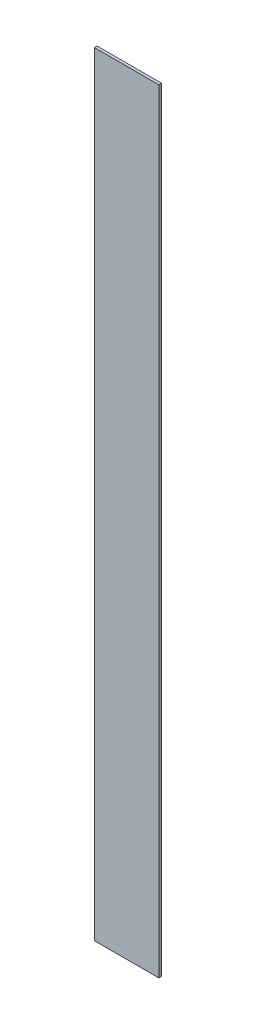
SolidWorks part; units mm, degrees
ref_plane "Front Plane" through (0, 0, 0) normal (0, 0, 1) x (1, 0, 0)
ref_plane "Top Plane" through (0, 0, 0) normal (0, 1, 0) x (1, 0, 0)
ref_plane "Right Plane" through (0, 0, 0) normal (1, 0, 0) x (0, 0, -1)
sketch "Sketch1" plane through (0, 0, 0) normal (0, 0, 1) x (1, 0, 0)
  line L1 (-38.1, -457.2) -> (38.1, -457.2)
  line L2 (-38.1, -457.2) -> (-38.1, 457.2)
  line L3 (-38.1, 457.2) -> (38.1, 457.2)
  line L4 (38.1, -457.2) -> (38.1, 457.2)
  line L5 (-38.1, -457.2) -> (38.1, 457.2) construction
  line L6 (-38.1, 457.2) -> (38.1, -457.2) construction
  point P0 (0, 0)
  dimension "D1" = 76.2
  dimension "D2" = 914.4
extrude "Boss-Extrude1" add sketch "Sketch1" along normal mid plane 3.175
